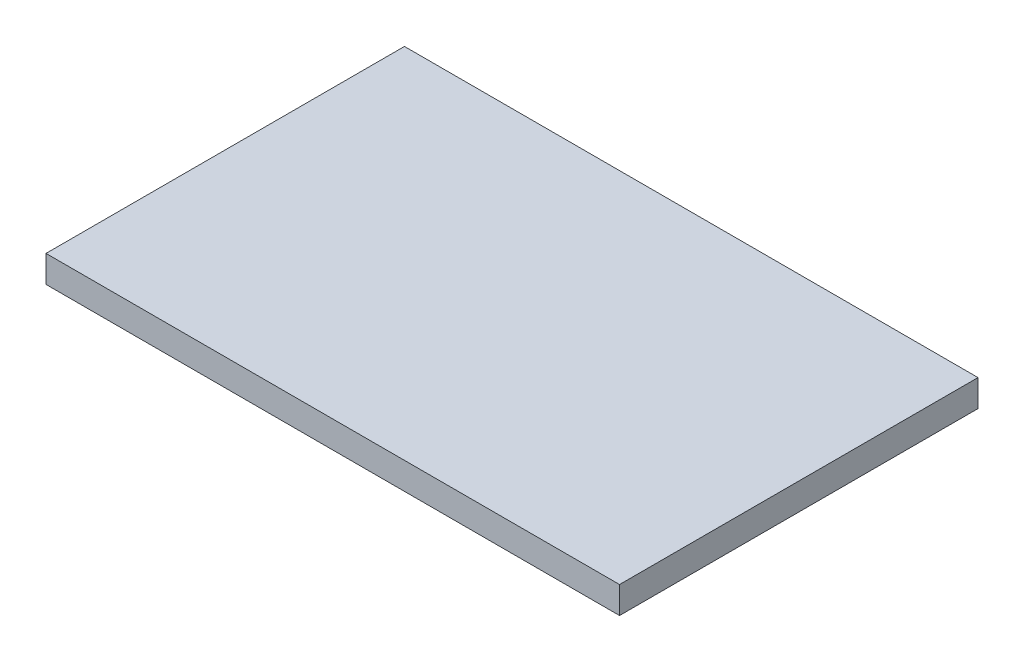
SolidWorks part; units mm, degrees
ref_plane "Front Plane" through (0, 0, 0) normal (0, 0, 1) x (1, 0, 0)
ref_plane "Top Plane" through (0, 0, 0) normal (0, 1, 0) x (1, 0, 0)
ref_plane "Right Plane" through (0, 0, 0) normal (1, 0, 0) x (0, 0, -1)
sketch "Sketch1" plane through (0, 0, 0) normal (0, 0, 1) x (1, 0, 0)
  line L1 (16, -0.75) -> (-16, -0.75)
  line L2 (16, -0.75) -> (16, 0.75)
  line L3 (16, 0.75) -> (-16, 0.75)
  line L4 (-16, -0.75) -> (-16, 0.75)
  line L5 (16, -0.75) -> (-16, 0.75) construction
  line L6 (16, 0.75) -> (-16, -0.75) construction
  point P0 (0, 0)
  point P5 (0, -0.75)
  point P6 (0, 0)
  dimension "D1" = 1.5
  dimension "D2" = 32
extrude "Boss-Extrude1" add sketch "Sketch1" along normal blind 20
